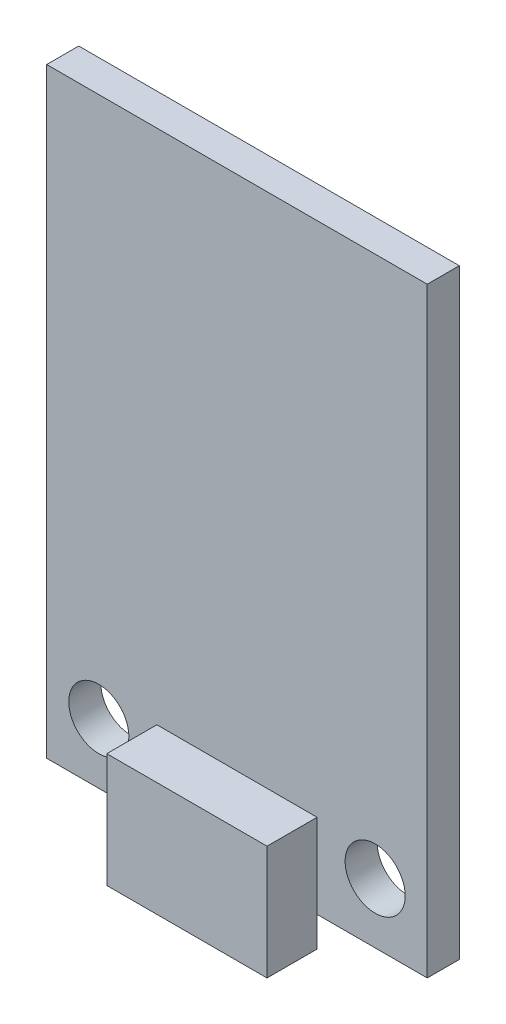
SolidWorks part; units mm, degrees
ref_plane "Plan de face" through (0, 0, 0) normal (0, 0, 1) x (1, 0, 0)
ref_plane "Plan de dessus" through (0, 0, 0) normal (0, 1, 0) x (1, 0, 0)
ref_plane "Plan de droite" through (0, 0, 0) normal (1, 0, 0) x (0, 0, -1)
sketch "Esquisse1" plane through (0, 0, 0) normal (0, 0, 1) x (1, 0, 0)
  line L1 (0, 0) -> (19, 0)
  line L2 (0, 0) -> (0, 30)
  line L3 (0, 30) -> (19, 30)
  line L4 (19, 0) -> (19, 30)
  dimension "D1" = 19
  dimension "D2" = 30
extrude "Boss.-Extru.1" add sketch "Esquisse1" along normal blind 1.6
sketch "Esquisse2" plane through (0, 0, 1.6) normal (0, 0, 1) x (1, 0, 0)
  line L0 (0, 0) -> (19, 0) construction
  line L1 (5.5, 4.2) -> (13.5, 4.2)
  line L2 (5.5, 4.2) -> (5.5, -1.5)
  line L3 (5.5, -1.5) -> (13.5, -1.5)
  line L4 (13.5, 4.2) -> (13.5, -1.5)
  point P6 (9.5, 0)
  point P7 (9.5, -1.5)
  dimension "D1" = 8
  dimension "D2" = 5.7
  dimension "D3" = 1.5
extrude "Boss.-Extru.2" add sketch "Esquisse2" along normal blind 2.5
sketch "Esquisse3" plane through (0, 0, 1.6) normal (0, 0, 1) x (1, 0, 0)
  line L0 (13.5, 0) -> (19, 0) construction
  line L1 (19, 0) -> (19, 30) construction
  line L2 (9.5, -1.5) -> (9.5, 30) construction
  line L3 (5.5, -1.5) -> (13.5, -1.5) construction
  line L4 (19, 30) -> (0, 30) construction
  circle A0 centre (16.4, 3) radius 1.5
  circle A1 centre (2.6, 3) radius 1.5
  dimension "D1" = 3
  dimension "D2" = 3
  dimension "D3" = 2.6
extrude "Enlèv. mat.-Extru.1" cut sketch "Esquisse3" against normal up to next
